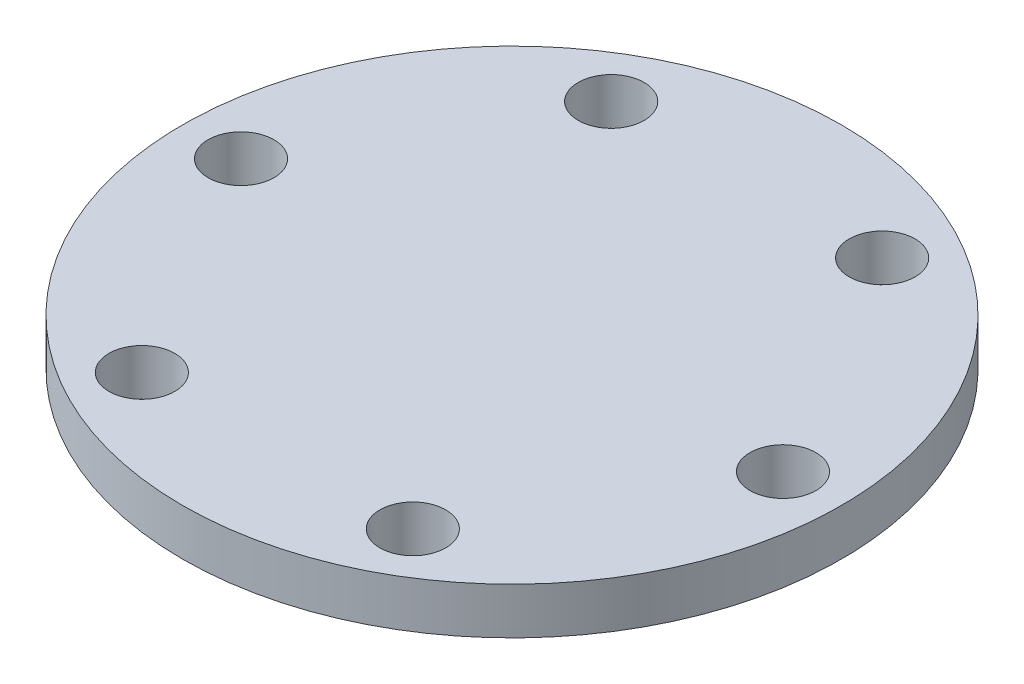
SolidWorks part; units mm, degrees
other "DetailItem2"
material "AISI 316 Stainless Steel Sheet (SS)"
ref_plane "Front Plane" through (0, 0, 0) normal (0, 0, 1) x (1, 0, 0)
ref_plane "Top Plane" through (0, 0, 0) normal (0, 1, 0) x (1, 0, 0)
ref_plane "Right Plane" through (0, 0, 0) normal (1, 0, 0) x (0, 0, -1)
ref_plane "40K Bottom Cold head Location" through (0, 236.49, 0) normal (0, 1, 0) x (1, 0, 0)
ref_plane "Top_Connection_Plane" through (22.5, 0, 0) normal (1, 0, 0) x (0, 0, -1)
ref_plane "Bottom_Connection_Plane" through (58, 0, 0) normal (1, 0, 0) x (0, 0, -1)
sketch "Sketch2" plane through (0, 236.49, 0) normal (0, 1, 0) x (1, 0, 0)
  line L0 (0, 22.5) -> (0, -22.5) construction
  line L1 (0, 0) -> (9.25, 16.0215) construction
  line L2 (0.25, 22.4986) -> (0.25, -22.4986)
  line L3 (-0.25, 22.4986) -> (-0.25, -22.4986)
  line L8 (-12.5, 26) -> (12.5, 26)
  line L9 (-22.5, 16) -> (-22.5, -16)
  line L10 (-12.5, -26) -> (12.5, -26)
  line L11 (22.5, 16) -> (22.5, -16)
  line L12 (13.325, 21.8331) -> (13.325, 18.1669) construction
  line L13 (-16.5, 20) -> (16.5, 20) construction
  line L14 (-16.5, 20) -> (-16.5, -20) construction
  line L15 (-16.5, -20) -> (16.5, -20) construction
  line L16 (16.5, 20) -> (16.5, -20) construction
  line L21 (0.25, 22.4986) -> (0.25, 26)
  line L22 (-0.25, 22.4986) -> (-0.25, 26)
  line L23 (13.325, 18.1669) -> (16.5, 16.3338) construction
  line L24 (16.5, 16.3338) -> (19.675, 18.1669) construction
  line L25 (19.675, 18.1669) -> (19.675, 21.8331) construction
  line L26 (19.675, 21.8331) -> (16.5, 23.6662) construction
  line L27 (16.5, 23.6662) -> (13.325, 21.8331) construction
  line L28 (16.5, 23.6662) -> (16.5, 16.3338) construction
  line L29 (0.25, -22.4986) -> (0.25, -26)
  line L30 (-0.25, -22.4986) -> (-0.25, -26)
  circle A1 centre (9.25, 16.0215) radius 2.25
  circle A5 centre (18.5, 0) radius 2.25
  circle A6 centre (9.25, -16.0215) radius 2.25
  circle A7 centre (-9.25, -16.0215) radius 2.25
  circle A8 centre (-18.5, 0) radius 2.25
  circle A9 centre (0, 0) radius 22.5
  circle A11 centre (-9.25, 16.0215) radius 2.25
  circle A12 centre (16.5, 20) radius 1.4732
  circle A13 centre (-16.5, 20) radius 1.4732
  circle A14 centre (-16.5, -20) radius 1.4732
  circle A15 centre (16.5, -20) radius 1.4732
  arc A16 (-22.5, -16) -> (-12.5, -26) centre (-12.5, -16) ccw
  arc A17 (12.5, -26) -> (22.5, -16) centre (12.5, -16) ccw
  arc A18 (-12.5, 26) -> (-22.5, 16) centre (-12.5, 16) ccw
  arc A19 (12.5, 26) -> (22.5, 16) centre (12.5, 16) cw
  circle A20 centre (16.5, 20) radius 2.3241 construction
  circle A21 centre (16.5, 20) radius 1.0934 construction
  point P22 (0, 0)
  point P25 (0, 0)
  point P28 (0, 26)
  point P29 (-22.5, 0)
  dimension "D3" = 4.5
  dimension "D8" = 45
  dimension "D12" = 2.9464
  dimension "D15" = 10
  dimension "D18" = 4.6482
  dimension "D2" = 18.5
  dimension "D4" = 30
  dimension "D10" = 0.25
  dimension "D6" = 18.5
  dimension "D7" = 18.5
  dimension "D9" = 0.25
  dimension "D11" = 3.5
  dimension "D13" = 6
  dimension "D14" = 6
  dimension "D16" = 6
  dimension "D17" = 6
  dimension "D20" = 6.35
  dimension "D21" = 6.35
  dimension "D5" = 6
extrude "Boss-Extrude1" add sketch "Sketch2" against normal blind 3.175 contours L3 A9 A11 A7 A8 | L2 A9 A1 A5 A6 | L2 A9 L3 | L9 A16 L10 A17 L11 A19 L8 A18
equation "\"Distance_From_Cold_Center\"=37.1"
equation "\"D10@Sketch1\"=\"Distance_From_Cold_Center\""
equation "\"D11@Sketch1\"=\"D2@Sketch1\"/2"
equation "\"Inside_Cold_Rod_Dia\"=52"
equation "\"40K_Cold_Head_Dia\"=45"
equation "\"D8@Sketch2\"=\"40K_Cold_Head_Dia\""
equation "\"D9@Sketch2\"=\"D10@Sketch2\""
equation "\"D14@Sketch2\"=\"D13@Sketch2\""
equation "\"D16@Sketch2\"=\"D13@Sketch2\""
equation "\"D17@Sketch2\"=\"D16@Sketch2\""
equation "\"D21@Sketch2\"=\"D20@Sketch2\""
